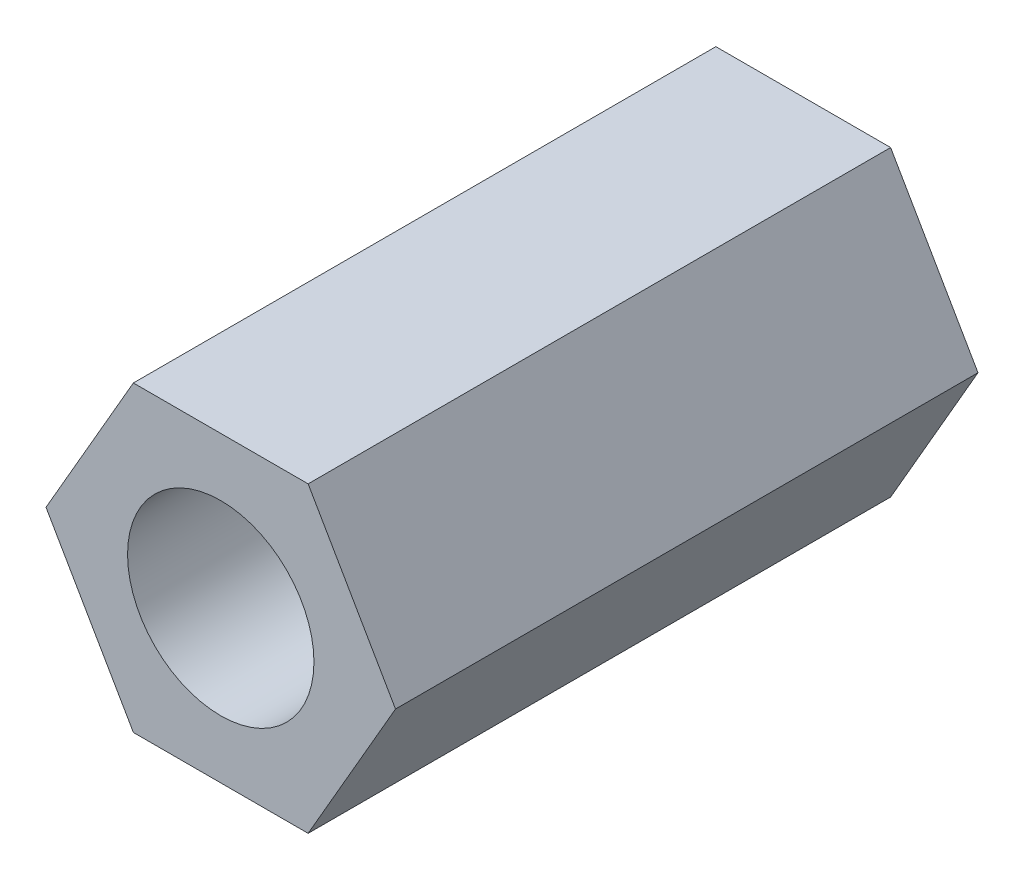
SolidWorks part; units mm, degrees
ref_plane "前视基准面" through (0, 0, 0) normal (0, 0, 1) x (1, 0, 0)
ref_plane "上视基准面" through (0, 0, 0) normal (0, 1, 0) x (1, 0, 0)
ref_plane "右视基准面" through (0, 0, 0) normal (1, 0, 0) x (0, 0, -1)
other "Configuration Table"
sketch "草图1" plane through (0, 0, 0) normal (0, 0, 1) x (1, 0, 0)
  line L1 (3, 0) -> (1.5, 2.5981)
  line L2 (1.5, 2.5981) -> (-1.5, 2.5981)
  line L3 (-1.5, 2.5981) -> (-3, 0)
  line L4 (-3, 0) -> (-1.5, -2.5981)
  line L5 (-1.5, -2.5981) -> (1.5, -2.5981)
  line L6 (1.5, -2.5981) -> (3, 0)
  circle A0 centre (0, 0) radius 1.6
  circle A1 centre (0, 0) radius 2.5981 construction
  dimension "D1" = 3.2
  dimension "D2" = 6
extrude "凸台-拉伸1" add sketch "草图1" along normal blind 10
